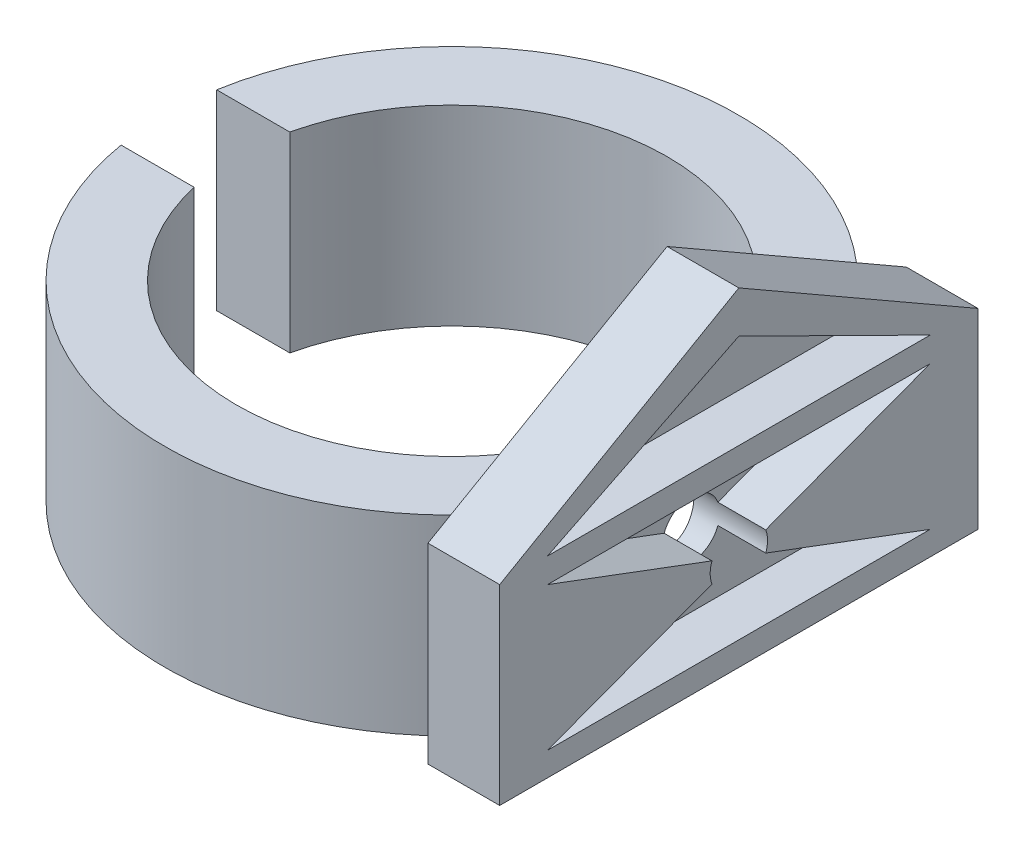
SolidWorks part; units mm, degrees
ref_plane "Front Plane" through (0, 0, 0) normal (0, 0, 1) x (1, 0, 0)
ref_plane "Top Plane" through (0, 0, 0) normal (0, 1, 0) x (1, 0, 0)
ref_plane "Right Plane" through (0, 0, 0) normal (1, 0, 0) x (0, 0, -1)
sketch "Sketch1" plane through (0, 0, 0) normal (0, 1, 0) x (1, 0, 0)
  circle A0 centre (0, 0) radius 22.5
  circle A1 centre (0, 0) radius 30
  dimension "D1" = 45
  dimension "D2" = 60
extrude "Boss-Extrude1" add sketch "Sketch1" along normal blind 20
ref_plane "Plane1" through (22.5, 0, 0) normal (1, 0, 0) x (0, 0, -1)
sketch "Sketch2" plane through (22.5, 0, 0) normal (1, 0, 0) x (0, 0, -1)
  line L1 (-25, 20) -> (25, 20)
  line L2 (-25, 20) -> (-25, 0)
  line L3 (-25, 0) -> (25, 0)
  line L4 (25, 20) -> (25, 0)
  line L5 (-25, 20) -> (25, 0) construction
  line L6 (-25, 0) -> (25, 20) construction
  point P0 (0, 10)
  dimension "D1" = 20
  dimension "D2" = 50
extrude "Boss-Extrude2" add sketch "Sketch2" along normal blind 7.5
ref_plane "Plane2" through (0, 0, 0) normal (0, 1, 0) x (1, 0, 0)
sketch "Sketch4" plane through (0, 0, 0) normal (0, 1, 0) x (1, 0, 0)
  line L0 (-60, 0) -> (0, 0) construction
  line L1 (0, 0) -> (0, 30) construction
  line L2 (0, 0) -> (0, -30) construction
  line L4 (-33.9902, 5) -> (-19.5916, 5)
  line L5 (-33.9902, 5) -> (-33.9902, -5)
  line L6 (-33.9902, -5) -> (-19.5916, -5)
  line L7 (-19.5916, 5) -> (-19.5916, -5)
  line L8 (-33.9902, 5) -> (-19.5916, -5) construction
  line L9 (-33.9902, -5) -> (-19.5916, 5) construction
  point P3 (-26.7909, 0)
  dimension "D1" = 5
  dimension "D2" = 5
extrude "Cut-Extrude1" cut sketch "Sketch4" along normal blind 20
ref_plane "Plane3" through (30, 0, 0) normal (1, 0, 0) x (0, 0, -1)
sketch "Sketch7" plane through (30, 0, 0) normal (1, 0, 0) x (0, 0, -1)
  line L0 (-1, 9.625) -> (-20, 2.5)
  line L1 (20, 2.5) -> (-20, 2.5)
  line L2 (20, 2.5) -> (20, 17.5) construction
  line L3 (20, 17.5) -> (-20, 17.5)
  line L4 (-20, 2.5) -> (-20, 17.5) construction
  line L5 (20, 2.5) -> (1, 9.625)
  line L6 (20, 17.5) -> (1, 10.375)
  line L8 (1, 10.375) -> (1, 9.625)
  line L10 (-1, 10.375) -> (-1, 9.625)
  line L13 (-1, 10.375) -> (-20, 17.5)
  point P0 (0, 10)
  point P6 (0, 10)
extrude "Cut-Extrude3" cut sketch "Sketch7" against normal blind 5
sketch "Sketch8" plane through (30, 0, 0) normal (1, 0, 0) x (0, 0, -1)
  circle A0 centre (0, 10) radius 3
extrude "Cut-Extrude4" cut sketch "Sketch8" against normal blind 10
sketch "Sketch9" plane through (30, 0, 0) normal (1, 0, 0) x (0, 0, -1)
  line L0 (-25, 20) -> (0, 34.3578)
  line L1 (25, 20) -> (0, 34.3578)
  line L2 (0, 10) -> (0, 46.3805) construction
  line L3 (-25, 20) -> (25, 20)
extrude "Boss-Extrude3" add sketch "Sketch9" against normal blind 7.5
sketch "Sketch10" plane through (30, 0, 0) normal (1, 0, 0) x (0, 0, -1)
  line L0 (-20, 20.0884) -> (20, 20.0884)
  line L1 (20, 20.0884) -> (0, 29.991)
  line L2 (0, 29.991) -> (-20, 20.0884)
  dimension "D1" = 40
  dimension "D2" = 0
extrude "Cut-Extrude5" cut sketch "Sketch10" against normal blind 5
